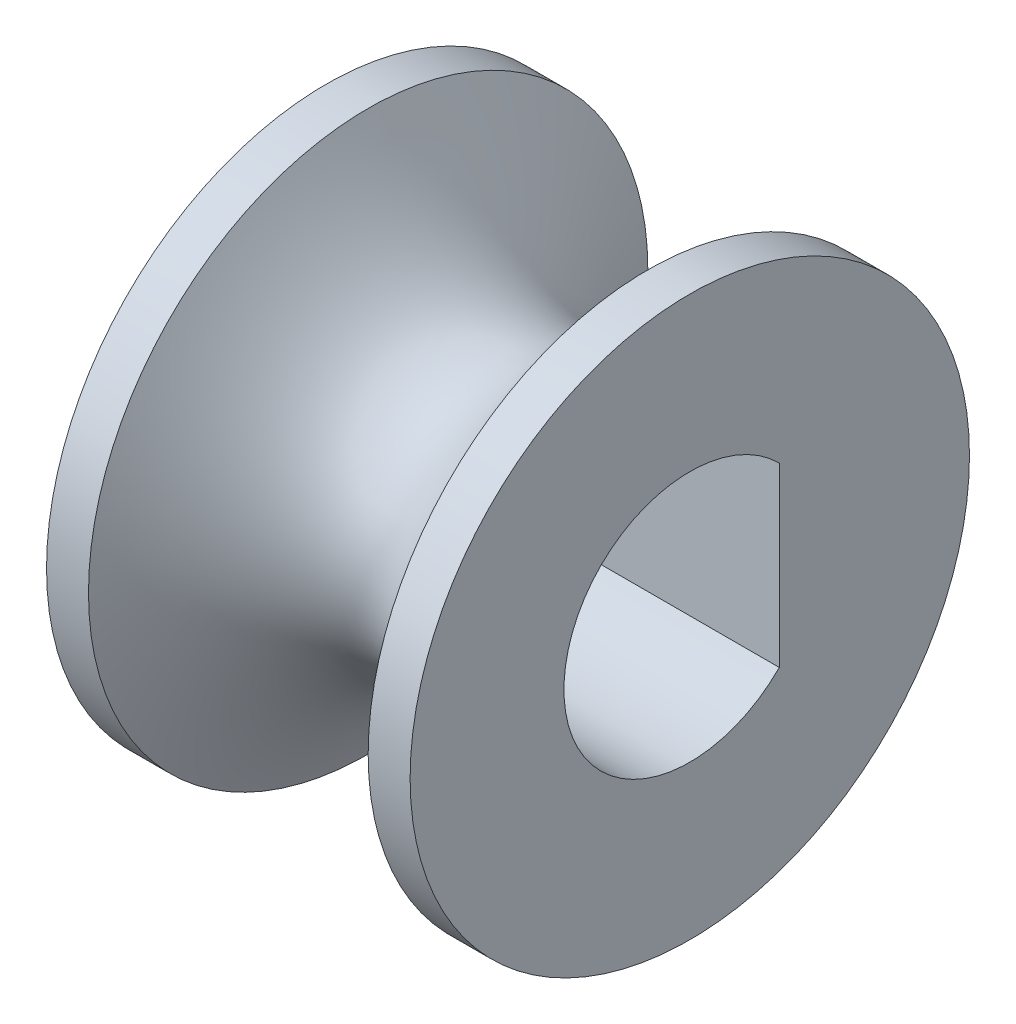
SolidWorks part; units mm, degrees
ref_plane "Front Plane" through (0, 0, 0) normal (0, 0, 1) x (1, 0, 0)
ref_plane "Top Plane" through (0, 0, 0) normal (0, 1, 0) x (1, 0, 0)
ref_plane "Right Plane" through (0, 0, 0) normal (1, 0, 0) x (0, 0, -1)
sketch "Sketch1" plane through (0, 0, 0) normal (0, 1, 0) x (1, 0, 0)
  line L0 (0, 0) -> (-2.5, 0)
  line L1 (-2.5, 0) -> (-3.25, 0)
  line L2 (-3.25, 0) -> (-3.25, 5)
  line L3 (2.5, 0) -> (0, 0)
  line L4 (-3.25, 5) -> (-2.5, 5)
  line L5 (2.5, 5) -> (3.25, 5)
  line L6 (3.25, 5) -> (3.25, 0)
  line L7 (3.25, 0) -> (2.5, 0)
  spline S0 degree 2 poles (-2.5, 5) (0, 0) (2.5, 5) knots 0 0 0 1 1 1
  dimension "D1" = 5
  dimension "D2" = 5
  dimension "D3" = 2.5
  dimension "D4" = 2.5
  dimension "D5" = 5
  dimension "D6" = 0.75
  dimension "D7" = 0.75
revolve "Revolve1" add sketch "Sketch1" angle 360 about L0
sketch "Sketch2" plane through (-3.25, 0, 0) normal (-1, 0, 0) x (0, 0, 1)
  line L0 (-1.6, -1.5819) -> (-1.6, 1.5819)
  arc A0 (-1.6, 1.5819) -> (-1.6, -1.5819) centre (0, 0) cw
  point P2 (2.25, 0)
  point P3 (-1.6, 0)
  dimension "D1" = 2.25
  dimension "D2" = 3.85
extrude "Cut-Extrude1" cut sketch "Sketch2" against normal blind 10
